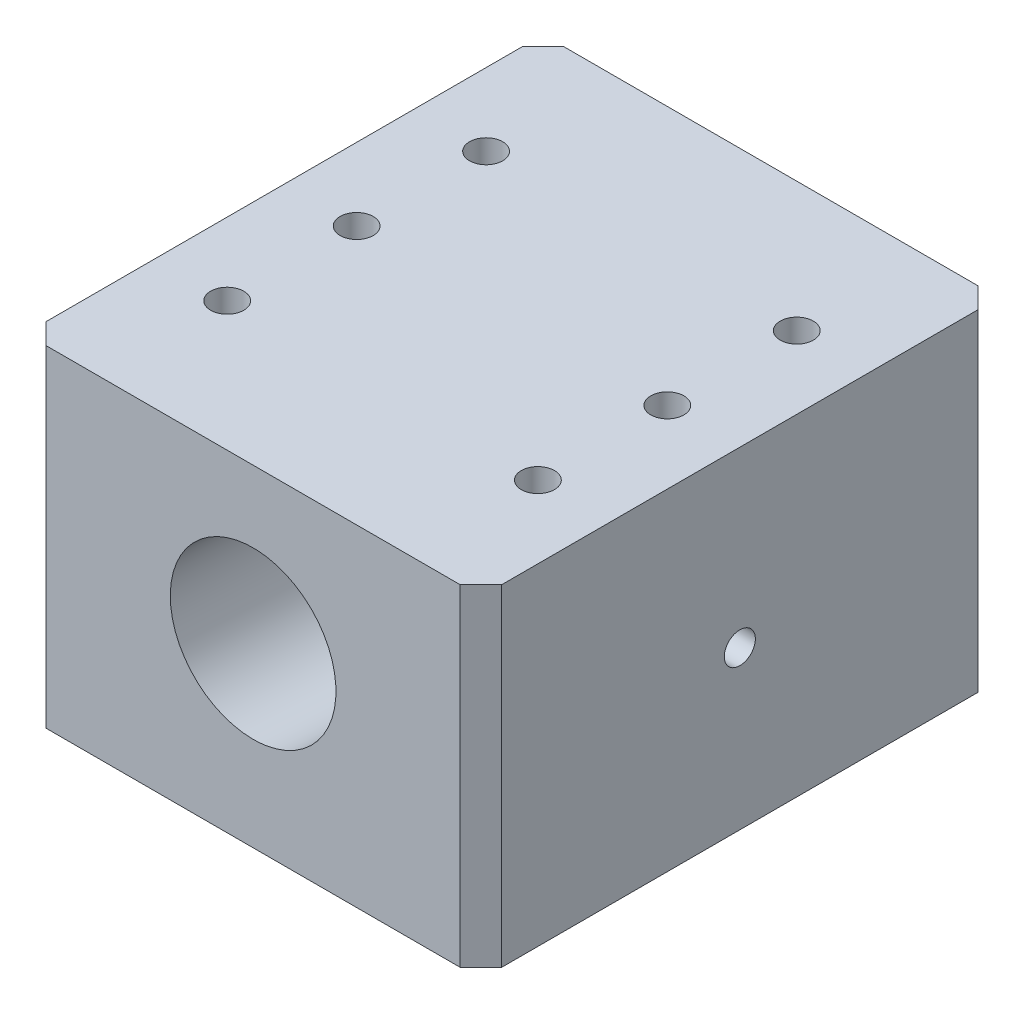
SolidWorks part; units mm, degrees
ref_plane "Ön Düzlem" through (0, 0, 0) normal (0, 0, 1) x (1, 0, 0)
ref_plane "Üst Düzlem" through (0, 0, 0) normal (0, 1, 0) x (1, 0, 0)
ref_plane "Sağ Düzlem" through (0, 0, 0) normal (1, 0, 0) x (0, 0, -1)
sketch "Çizim1" plane through (0, 0, 0) normal (0, 0, 1) x (1, 0, 0)
  line L1 (-22, -16) -> (22, -16)
  line L2 (-22, -16) -> (-22, 16)
  line L3 (-22, 16) -> (22, 16)
  line L4 (22, -16) -> (22, 16)
  line L5 (-22, -16) -> (22, 16) construction
  line L6 (-22, 16) -> (22, -16) construction
  point P0 (0, 0)
  dimension "D1" = 44
  dimension "D2" = 32
extrude "Yükseklik-Ekstrüzyon1" add sketch "Çizim1" against normal blind 50
ref_plane "Düzlem1" through (0, 0.0438, 0.8362) normal (0, 0.0523, 0.9986) x (-1, 0, 0)
sketch "Çizim2" plane through (0, 0.0438, 0.8362) normal (0, 0.0523, 0.9986) x (-1, 0, 0)
  line L0 (0, -15.9781) -> (0, 16.0219) construction
  line L1 (-22, -15.9781) -> (22, -15.9781) construction
  circle A0 centre (0, -1.08) radius 8
  dimension "D2" = 16
  dimension "D1" = 32
  dimension "D3" = 1.08
extrude "Kes-Ekstrüzyon1" cut sketch "Çizim2" against normal blind 60 and the other way blind 56
sketch "Çizim4" plane through (0, 16, 0) normal (0, 1, 0) x (1, 0, 0)
  line L0 (0, 0) -> (0, 50) construction
  line L1 (22, 50) -> (-22, 50) construction
  line L2 (0, 50) -> (-8, 50) construction
  line L3 (-8, 50) -> (-8, 0) construction
  line L4 (22, 0) -> (-22, 0) construction
  line L5 (-8, 0) -> (-22, 0) construction
  line L6 (-15, 0) -> (-15, 50) construction
  circle A0 centre (-15, 25) radius 1.6
  circle A1 centre (-15, 37.5) radius 1.6
  circle A2 centre (-15, 12.5) radius 1.6
  circle A3 centre (15, 12.5) radius 1.6
  circle A4 centre (15, 37.5) radius 1.6
  circle A5 centre (15, 25) radius 1.6
  dimension "D2" = 3.2
  dimension "D1" = 8
  dimension "D3" = 12.5
  dimension "D4" = 12.5
extrude "Kes-Ekstrüzyon2" cut sketch "Çizim4" against normal blind 60
sketch "Çizim5" plane through (0, 0, 0) normal (1, 0, 0) x (0, 0, -1)
  line L0 (0, 0) -> (50, -1.5389) construction
  line L1 (50, -9.5499) -> (50, 6.4721) construction
  circle A0 centre (25, -0.7695) radius 1.5
  dimension "D1" = 3
extrude "Kes-Ekstrüzyon3" cut sketch "Çizim5" against normal mid plane 90
chamfer "Pah1" distance 2 angle 45 4 edges at (22, 0, -50) (-22, 0, -50) (-22, 0, 0) (22, 0, 0)
